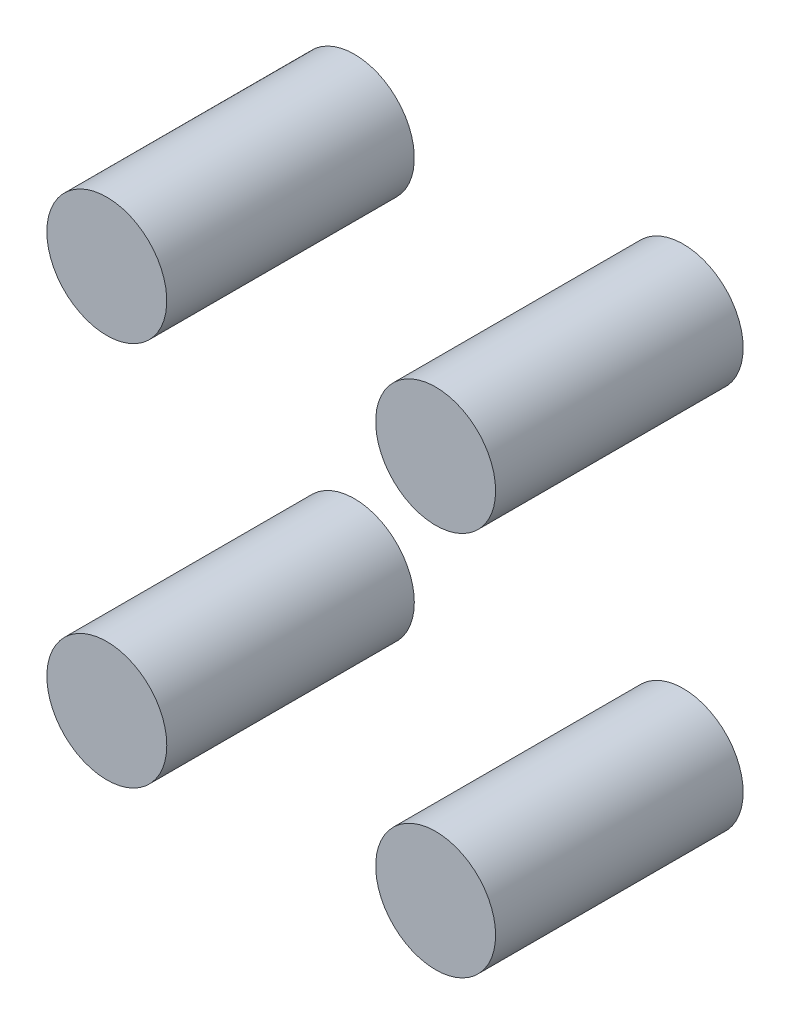
SolidWorks part; units mm, degrees
ref_plane "Front Plane" through (0, 0, 0) normal (0, 0, 1) x (1, 0, 0)
ref_plane "Top Plane" through (0, 0, 0) normal (0, 1, 0) x (1, 0, 0)
ref_plane "Right Plane" through (0, 0, 0) normal (1, 0, 0) x (0, 0, -1)
sketch "Sketch1" plane through (0, 0, 0) normal (0, 0, 1) x (1, 0, 0)
  line L0 (-0.3162, 0.0504) -> (-0.3162, 81.4506) construction
  line L5 (52.8185, 0.0504) -> (52.8185, 81.4506) construction
  circle A8 centre (-0.3162, 0.0504) radius 9.6889
  circle A9 centre (52.8185, 0.0504) radius 9.6889
  circle A10 centre (52.8185, 62.2403) radius 9.6889
  circle A11 centre (-0.3162, 62.2403) radius 9.6889
  point P4 (0, 0)
  point P5 (-0.3162, 76.5458)
  point P6 (53.636, 62.2403)
  point P7 (-0.7249, 62.2403)
  point P8 (-0.3162, 81.4506)
  point P9 (52.8185, 81.4506)
extrude "Boss-Extrude1" add sketch "Sketch1" along normal blind 40 contours A10 | A9 | A11 | A8
